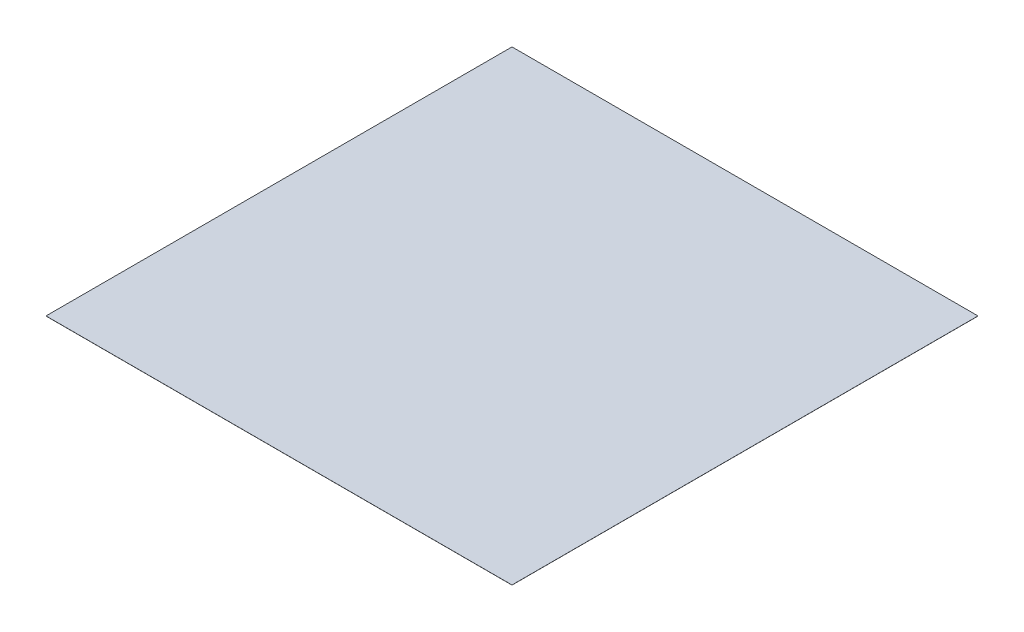
SolidWorks part; units mm, degrees
ref_plane "前视基准面" through (0, 0, 0) normal (0, 0, 1) x (1, 0, 0)
ref_plane "上视基准面" through (0, 0, 0) normal (0, 1, 0) x (1, 0, 0)
ref_plane "右视基准面" through (0, 0, 0) normal (1, 0, 0) x (0, 0, -1)
other "Configuration Table"
sketch "草图1" plane through (0, 0, 0) normal (0, 1, 0) x (1, 0, 0)
  line L1 (-400, -400) -> (400, -400)
  line L2 (-400, -400) -> (-400, 400)
  line L3 (-400, 400) -> (400, 400)
  line L4 (400, -400) -> (400, 400)
  line L5 (-400, -400) -> (400, 400) construction
  line L6 (-400, 400) -> (400, -400) construction
  point P0 (0, 0)
  dimension "D1" = 800
extrude "凸台-拉伸1" add sketch "草图1" along normal blind 0.2
